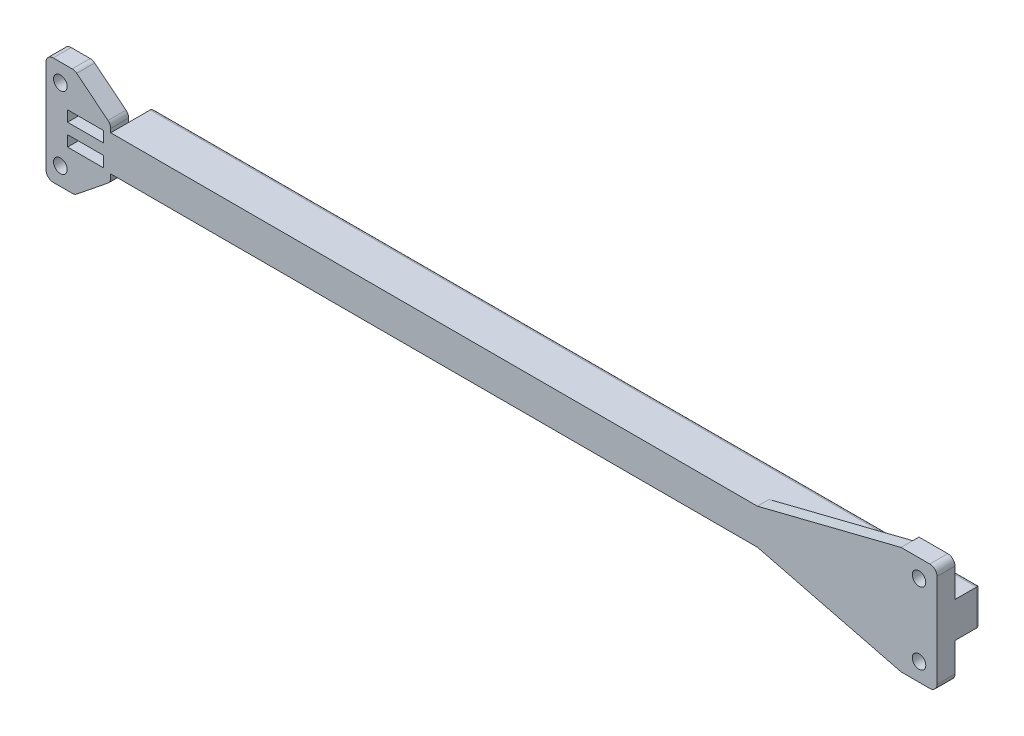
SolidWorks part; units mm, degrees
ref_plane "Front Plane" through (0, 0, 0) normal (0, 0, 1) x (1, 0, 0)
ref_plane "Top Plane" through (0, 0, 0) normal (0, 1, 0) x (1, 0, 0)
ref_plane "Right Plane" through (0, 0, 0) normal (1, 0, 0) x (0, 0, -1)
sketch "Sketch1" plane through (0, 0, 0) normal (0, 0, 1) x (1, 0, 0)
  line L1 (-292.1, -6.2865) -> (-12.7, -6.2865)
  line L2 (-292.1, 6.2865) -> (-12.7, 6.2865)
  line L8 (-292.1, -6.2865) -> (-292.1, -8.8265)
  line L9 (-304.8, 19.05) -> (-314.96, 19.05)
  line L10 (-292.1, 8.8265) -> (-292.1, 6.2865)
  line L11 (-304.8, -19.05) -> (-314.96, -19.05)
  line L12 (-314.96, 19.05) -> (-314.96, -19.05)
  line L13 (-307.34, 1.905) -> (-294.64, 1.905)
  line L14 (-307.34, 1.905) -> (-307.34, 5.715)
  line L15 (-307.34, 5.715) -> (-294.64, 5.715)
  line L16 (-294.64, 1.905) -> (-294.64, 5.715)
  line L17 (-292.1, -8.8265) -> (-304.8, -19.05)
  line L18 (-292.1, 8.8265) -> (-304.8, 19.05)
  line L24 (-314.96, 0) -> (0, 0) construction
  line L25 (-294.64, -1.905) -> (-294.64, -5.715)
  line L26 (-307.34, -5.715) -> (-294.64, -5.715)
  line L27 (-307.34, -1.905) -> (-307.34, -5.715)
  line L28 (-307.34, -1.905) -> (-294.64, -1.905)
  line L29 (-12.7, -6.2865) -> (-12.7, -19.05)
  line L30 (0, 19.05) -> (-12.7, 19.05)
  line L31 (0, 19.05) -> (0, -19.05)
  line L32 (0, -19.05) -> (-12.7, -19.05)
  line L33 (-12.7, 19.05) -> (-12.7, 6.2865)
  line L34 (-12.7, 6.2865) -> (-12.7, -6.2865) construction
  circle A2 centre (-309.88, -12.7) radius 2.413
  circle A4 centre (-309.88, 12.7) radius 2.413
  circle A5 centre (-6.35, 12.7) radius 2.3813
  circle A6 centre (-6.35, -12.7) radius 2.3813
  point P0 (0, 0)
  point P4 (-12.7, 0)
  point P7 (-6.35, 19.05)
  point P22 (-6.35, -19.05)
  point P31 (-309.88, -19.05)
  point P32 (-314.96, 0)
  dimension "D3" = 292.1
  dimension "D8" = 38.1
  dimension "D9" = 4.826
  dimension "D17" = 4.7625
  dimension "D2" = 12.7
  dimension "D4" = 12.573
  dimension "D5" = 1.905
  dimension "D6" = 12.7
  dimension "D7" = 38.1
  dimension "D10" = 5.08
  dimension "D11" = 3.81
  dimension "D12" = 12.7
  dimension "D13" = 7.62
  dimension "D14" = 2.54
  dimension "D15" = 10.16
  dimension "D16" = 22.86
  dimension "D18" = 12.7
extrude "Boss-Extrude1" add sketch "Sketch1" along normal mid plane 6.35
sketch "Sketch3" plane through (0, 0, -3.175) normal (0, 0, -1) x (-1, 0, 0)
  line L0 (292.1, -6.2865) -> (12.7, -6.2865) construction
  line L1 (0, 6.2865) -> (292.1, 6.2865)
  line L2 (0, 6.2865) -> (0, -6.2865)
  line L3 (0, -6.2865) -> (292.1, -6.2865)
  line L4 (292.1, 6.2865) -> (292.1, -6.2865)
  line L5 (0, -19.05) -> (0, 19.05) construction
extrude "Boss-Extrude2" add sketch "Sketch3" along normal blind 8.89
sketch "Sketch2" plane through (0, 0, 0) normal (0, 1, 0) x (1, 0, 0)
  line L0 (-300.99, 4.445) -> (-300.99, -3.175) construction
  line L1 (-8.7313, -3.175) -> (-3.9688, -3.175) construction
  line L2 (-307.34, -3.175) -> (-294.64, -3.175) construction
  circle A0 centre (-300.99, 4.445) radius 5.08
  dimension "D1" = 10.16
  dimension "D2" = 7.62
extrude "Cut-Extrude1" [suppressed] cut sketch "Sketch2" against normal mid plane 16.51
sketch "Sketch4" plane through (0, 0, 3.175) normal (0, 0, 1) x (1, 0, 0)
  line L0 (-12.7, 19.05) -> (-63.5, 6.2865)
  line L1 (-292.1, 6.2865) -> (0, 6.2865) construction
  line L2 (-63.5, 6.2865) -> (-12.7, 6.2865)
  line L3 (-12.7, 6.2865) -> (-12.7, 19.05)
  line L4 (0, 0) -> (-314.96, 0) construction
  line L6 (-314.96, 19.05) -> (-314.96, -19.05) construction
  line L7 (-12.7, -6.2865) -> (-12.7, -19.05)
  line L8 (-63.5, -6.2865) -> (-12.7, -6.2865)
  line L9 (-12.7, -19.05) -> (-63.5, -6.2865)
  dimension "D1" = 50.8
extrude "Boss-Extrude3" add sketch "Sketch4" against normal blind 4.1275 contours L3 L0 L2 | L7 L9 L8
fillet "Fillet1" radius 2.54 8 edges at (-292.1, 8.8265, 0) (-292.1, -8.8265, 0) (-304.8, -19.05, 0) (-314.96, -19.05, 0) (-314.96, 19.05, 0) (-304.8, 19.05, 0) (0, -19.05, 0) (0, 19.05, 0)
mirror "Mirror1" [suppressed] about plane through (0, 0, 0) normal (0, 0, 1)
fillet "Fillet2" radius 1.27 4 edges at (-146.05, 6.2865, -12.065) (-292.1, 0, -12.065) (-146.05, -6.2865, -12.065) (0, 0, -12.065)
